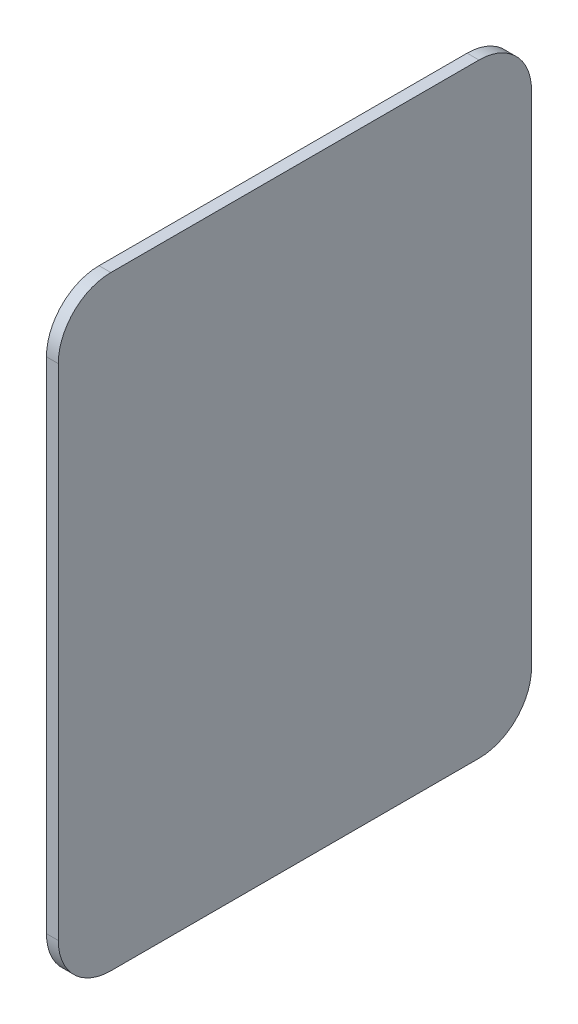
SolidWorks part; units mm, degrees
ref_plane "前视基准面" through (0, 0, 0) normal (0, 0, 1) x (1, 0, 0)
ref_plane "上视基准面" through (0, 0, 0) normal (0, 1, 0) x (1, 0, 0)
ref_plane "右视基准面" through (0, 0, 0) normal (1, 0, 0) x (0, 0, -1)
sketch "草图1" plane through (0, 0, 0) normal (1, 0, 0) x (0, 0, -1)
  line L1 (70, -115) -> (-70, -115)
  line L2 (90, -95) -> (90, 95)
  line L3 (70, 115) -> (-70, 115)
  line L4 (-90, -95) -> (-90, 95)
  line L5 (90, -115) -> (-90, 115) construction
  line L6 (90, 115) -> (-90, -115) construction
  arc A0 (-70, -115) -> (-90, -95) centre (-70, -95) cw
  arc A1 (70, -115) -> (90, -95) centre (70, -95) ccw
  arc A2 (90, 95) -> (70, 115) centre (70, 95) ccw
  arc A3 (-70, 115) -> (-90, 95) centre (-70, 95) ccw
  point P0 (0, 0)
  dimension "D3" = 20
  dimension "D1" = 180
  dimension "D2" = 230
extrude "凸台-拉伸1" add sketch "草图1" along normal blind 4.5
